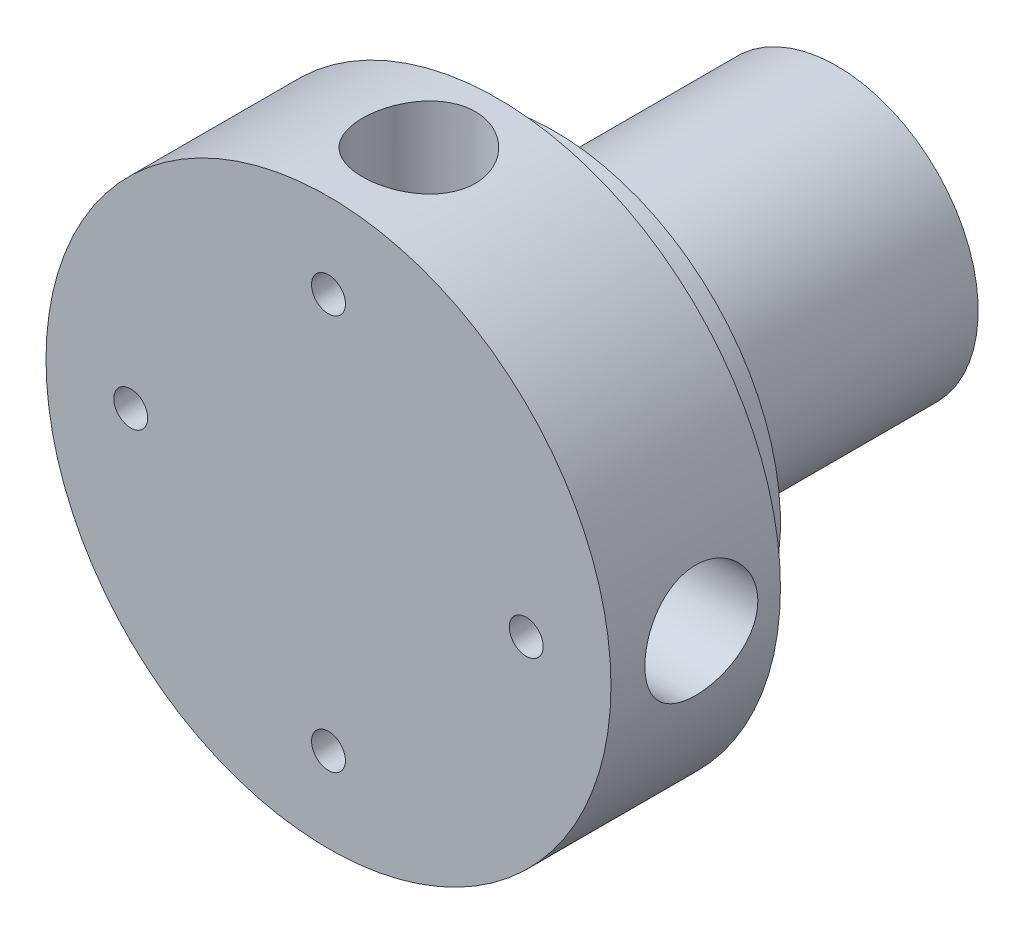
SolidWorks part; units mm, degrees
ref_plane "Ön Düzlem" through (0, 0, 0) normal (0, 0, 1) x (1, 0, 0)
ref_plane "Üst Düzlem" through (0, 0, 0) normal (0, 1, 0) x (1, 0, 0)
ref_plane "Sağ Düzlem" through (0, 0, 0) normal (1, 0, 0) x (0, 0, -1)
sketch "Sketch1" plane through (0, 0, 0) normal (0, 0, 1) x (1, 0, 0)
  circle A0 centre (0, 0) radius 25
  dimension "D1" = 50
extrude "Boss-Extrude1" add sketch "Sketch1" along normal blind 15
sketch "Sketch2" plane through (0, 0, 0) normal (0, 1, 0) x (1, 0, 0)
  line L0 (-25, -15) -> (25, -15) construction
  circle A0 centre (0, -7) radius 5
  dimension "D1" = 10
  dimension "D2" = 8
extrude "Cut-Extrude1" cut sketch "Sketch2" against normal blind 60 from offset 10 offset against normal yes
sketch "Sketch8" plane through (0, 0, 0) normal (0, 0, -1) x (-1, 0, 0)
  circle A0 centre (0, 0) radius 20
  dimension "D1" = 40
extrude "Boss-Extrude4" add sketch "Sketch8" along normal blind 5
sketch "Sketch3" plane through (0, 0, 15) normal (0, 0, 1) x (1, 0, 0)
  line L0 (-5, -10) -> (5, -10) construction
  circle A0 centre (0, -17.5) radius 1.5
  dimension "D1" = 3
  dimension "D2" = 7.5
extrude "Cut-Extrude2" cut sketch "Sketch3" against normal blind 20
pattern_circular "CirPattern2" count 4 over 360 about axis through (0, 0, 0) along (0, 0, 1) of "Cut-Extrude1", "Cut-Extrude2"
sketch "Sketch4" plane through (0, 0, 0) normal (0, 0, -1) x (-1, 0, 0)
  circle A0 centre (0, 0) radius 12.5
  dimension "D1" = 25
extrude "Boss-Extrude2" add sketch "Sketch4" along normal blind 30
sketch "Sketch7" plane through (0, 0, 0) normal (1, 0, 0) x (0, 0, -1)
  line L0 (30, -12.5) -> (30, 12.5) construction
  circle A0 centre (27, 0) radius 1.5
  dimension "D1" = 3
  dimension "D2" = 3
extrude "Cut-Extrude4" cut sketch "Sketch7" against normal blind 15 from offset 5 offset against normal yes
fillet "Fillet3" radius 2 1 edges at (-12.5, 0, -5)
